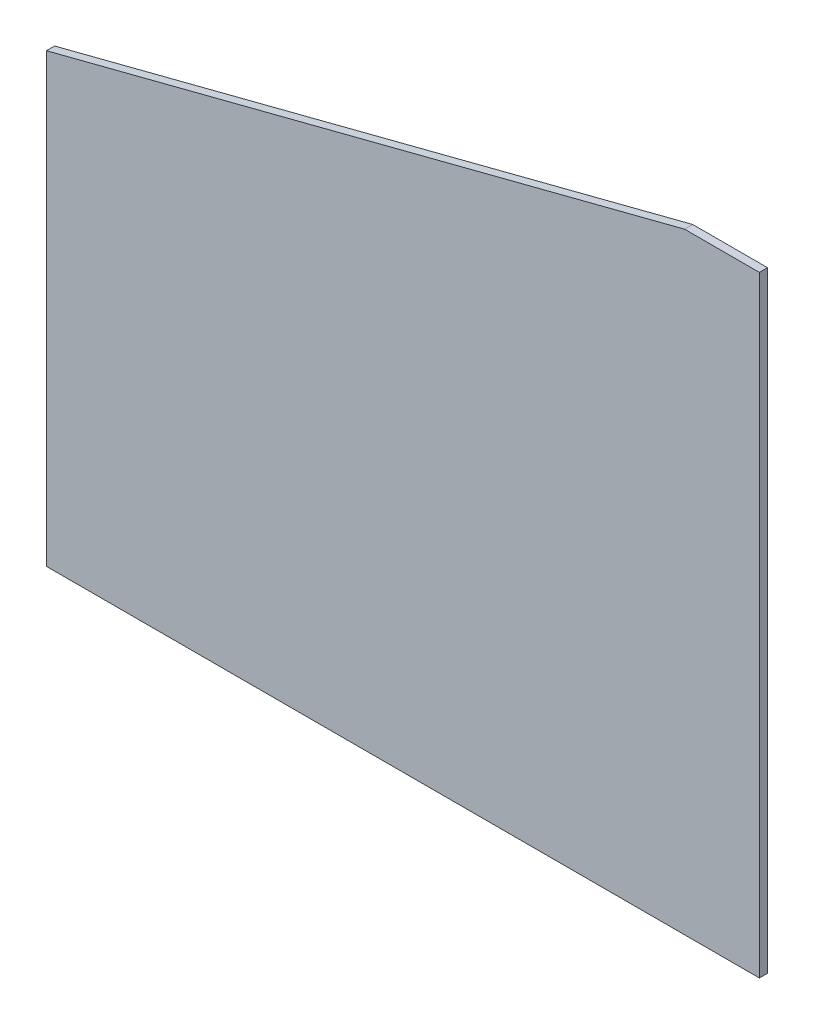
SolidWorks part; units mm, degrees
ref_plane "Ebene vorne" through (0, 0, 0) normal (0, 0, 1) x (1, 0, 0)
ref_plane "Ebene oben" through (0, 0, 0) normal (0, 1, 0) x (1, 0, 0)
ref_plane "Ebene rechts" through (0, 0, 0) normal (1, 0, 0) x (0, 0, -1)
sketch "Skizze1" plane through (0, 0, 0) normal (0, 0, 1) x (1, 0, 0)
  line L0 (0, 0) -> (0, 877)
  line L1 (0, 877) -> (1252.9774, 1200)
  line L2 (1252.9774, 1200) -> (1400, 1200)
  line L3 (1400, 1200) -> (1400, 0)
  line L4 (1400, 0) -> (0, 0)
  dimension "D1" = 877
  dimension "D2" = 1400
  dimension "D3" = 1200
extrude "Aufsatz-Linear austragen1" add sketch "Skizze1" along normal blind 16
